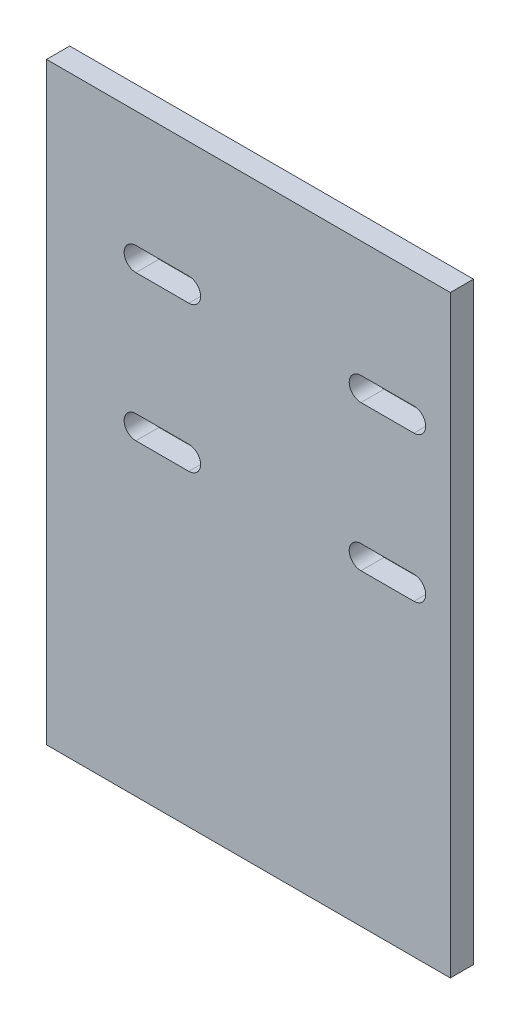
SolidWorks part; units mm, degrees
ref_plane "Front Plane" through (0, 0, 0) normal (0, 0, 1) x (1, 0, 0)
ref_plane "Top Plane" through (0, 0, 0) normal (0, 1, 0) x (1, 0, 0)
ref_plane "Right Plane" through (0, 0, 0) normal (1, 0, 0) x (0, 0, -1)
sketch "Sketch1" plane through (0, 0, 0) normal (0, 0, 1) x (1, 0, 0)
  line L0 (268.1742, -214.3409) -> (268.1742, -25.8475) construction
  line L1 (99.8992, -25.8475) -> (293.5742, -25.8475)
  line L2 (99.8992, -25.8475) -> (99.8992, -297.8658)
  line L3 (99.8992, -297.8658) -> (293.5742, -297.8658) construction
  line L4 (293.5742, -25.8475) -> (293.5742, -297.8658)
  line L5 (142.7617, -157.1909) -> (168.1617, -157.1909) construction
  line L6 (142.7617, -152.8253) -> (168.1617, -152.8253) construction
  line L7 (142.7617, -161.5565) -> (168.1617, -161.5565) construction
  line L8 (142.7617, -151.5553) -> (168.1617, -151.5553)
  line L11 (142.7617, -162.8265) -> (168.1617, -162.8265)
  line L12 (142.7617, -87.3409) -> (168.1617, -87.3409) construction
  line L13 (142.7617, -81.7053) -> (168.1617, -81.7053)
  line L14 (142.7617, -92.9765) -> (168.1617, -92.9765)
  line L15 (276.1117, -87.3409) -> (250.7117, -87.3409) construction
  line L16 (276.1117, -92.9765) -> (250.7117, -92.9765)
  line L17 (276.1117, -81.7053) -> (250.7117, -81.7053)
  line L18 (276.1117, -157.1909) -> (250.7117, -157.1909) construction
  line L19 (276.1117, -162.8265) -> (250.7117, -162.8265)
  line L20 (276.1117, -151.5553) -> (250.7117, -151.5553)
  line L21 (132.1572, -25.8475) -> (284.5572, -25.8475) construction
  line L22 (99.8992, -297.8658) -> (293.5742, -297.8658) construction
  line L23 (99.8992, -297.8658) -> (99.8992, -310.5658)
  line L24 (99.8992, -310.5658) -> (293.5742, -310.5658)
  line L25 (293.5742, -297.8658) -> (293.5742, -310.5658)
  line L26 (99.8992, -25.8475) -> (99.8992, -259.7658) construction
  arc A0 (142.7617, -152.8253) -> (142.7617, -161.5565) centre (142.7617, -157.1909) ccw construction
  arc A1 (168.1617, -161.5565) -> (168.1617, -152.8253) centre (168.1617, -157.1909) ccw construction
  circle A6 centre (142.7617, -157.1909) radius 4.3656 construction
  arc A7 (168.1617, -162.8265) -> (168.1617, -151.5553) centre (168.1617, -157.1909) ccw
  arc A8 (142.7617, -151.5553) -> (142.7617, -162.8265) centre (142.7617, -157.1909) ccw
  arc A9 (142.7617, -81.7053) -> (142.7617, -92.9765) centre (142.7617, -87.3409) ccw
  arc A10 (168.1617, -92.9765) -> (168.1617, -81.7053) centre (168.1617, -87.3409) ccw
  arc A11 (276.1117, -92.9765) -> (276.1117, -81.7053) centre (276.1117, -87.3409) ccw
  arc A12 (250.7117, -81.7053) -> (250.7117, -92.9765) centre (250.7117, -87.3409) ccw
  arc A13 (276.1117, -162.8265) -> (276.1117, -151.5553) centre (276.1117, -157.1909) ccw
  arc A14 (250.7117, -151.5553) -> (250.7117, -162.8265) centre (250.7117, -157.1909) ccw
  circle A15 centre (250.7117, -157.1909) radius 4.3656 construction
  circle A16 centre (250.7117, -87.3409) radius 4.3656 construction
  circle A17 centre (142.7617, -87.3409) radius 4.3656 construction
  point P9 (155.4617, -157.1909)
  point P24 (155.4617, -87.3409)
  point P33 (263.4117, -87.3409)
  point P41 (263.4117, -157.1909)
  dimension "D1" = 25.4
  dimension "D2" = 25.4
  dimension "D4" = 12.7
  dimension "D3" = 1.27
extrude "Boss-Extrude1" add sketch "Sketch1" against normal blind 11.1125 from surface contours L25 L4 L1 L2 L23 L24 A14 L20 A13 L19 A12 L17 A11 L16 A10 L14 A9 L13 A8 L8 A7 L11
